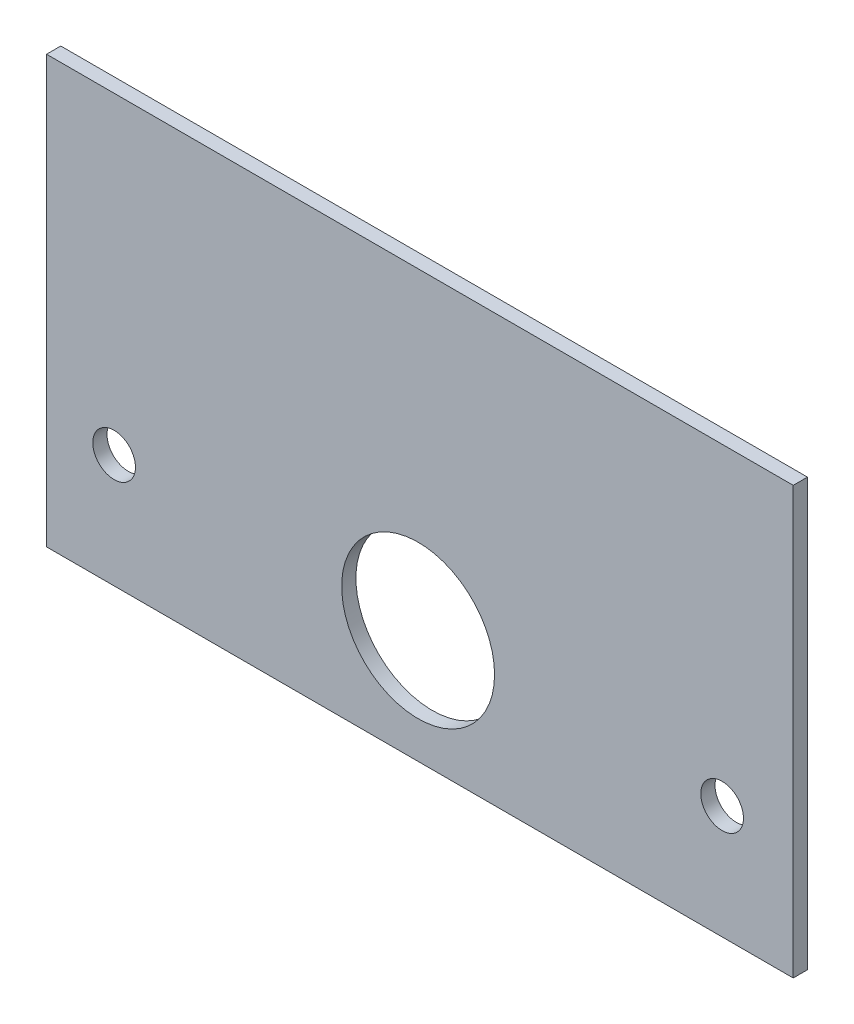
SolidWorks part; units mm, degrees
ref_plane "Front Plane" through (0, 0, 0) normal (0, 0, 1) x (1, 0, 0)
ref_plane "Top Plane" through (0, 0, 0) normal (0, 1, 0) x (1, 0, 0)
ref_plane "Right Plane" through (0, 0, 0) normal (1, 0, 0) x (0, 0, -1)
sketch "Sketch1" plane through (0, 0, 0) normal (0, 0, 1) x (1, 0, 0)
  line L1 (0, 0) -> (-105, 0)
  line L2 (0, 0) -> (0, -60)
  line L3 (0, -60) -> (-105, -60)
  line L4 (-105, 0) -> (-105, -60)
  circle A0 centre (-10, -44.05) radius 3
  circle A1 centre (-52.75, -44.05) radius 10.75
  circle A2 centre (-95.5, -44.05) radius 3
  dimension "D3" = 6
  dimension "D4" = 21.5
  dimension "D5" = 6
  dimension "D6" = 10
  dimension "D7" = 42.75
  dimension "D8" = 42.75
  dimension "D9" = 44.05
  dimension "D10" = 44.05
  dimension "D11" = 44.05
  dimension "D1" = 60
  dimension "D2" = 105
extrude "Boss-Extrude1" add sketch "Sketch1" along normal blind 2
